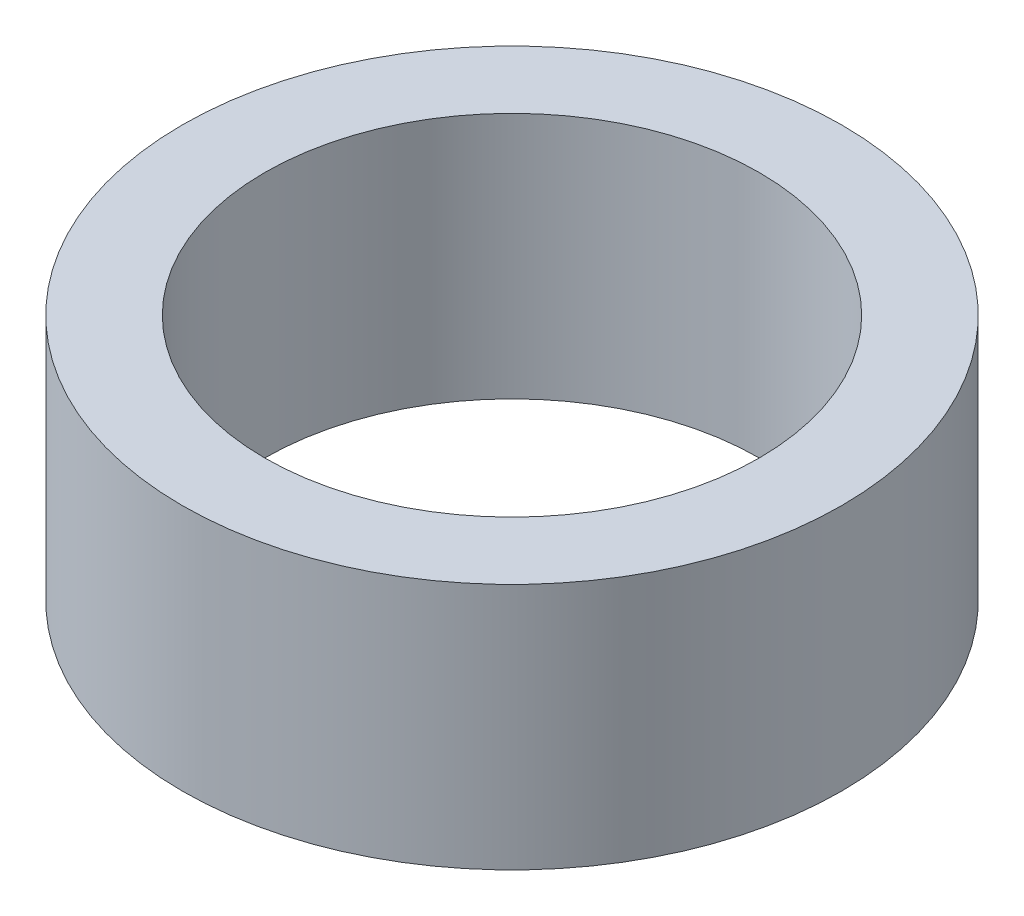
SolidWorks part; units mm, degrees
ref_plane "Plan de face" through (0, 0, 0) normal (0, 0, 1) x (1, 0, 0)
ref_plane "Plan de dessus" through (0, 0, 0) normal (0, 1, 0) x (1, 0, 0)
ref_plane "Plan de droite" through (0, 0, 0) normal (1, 0, 0) x (0, 0, -1)
sketch "Esquisse1" plane through (0, 0, 0) normal (0, 1, 0) x (1, 0, 0)
  circle A0 centre (0, 0) radius 2.25
  circle A1 centre (0, 0) radius 3
  dimension "D1" = 4.5
  dimension "D2" = 6
extrude "Boss.-Extru.1" add sketch "Esquisse1" along normal blind 2.25
